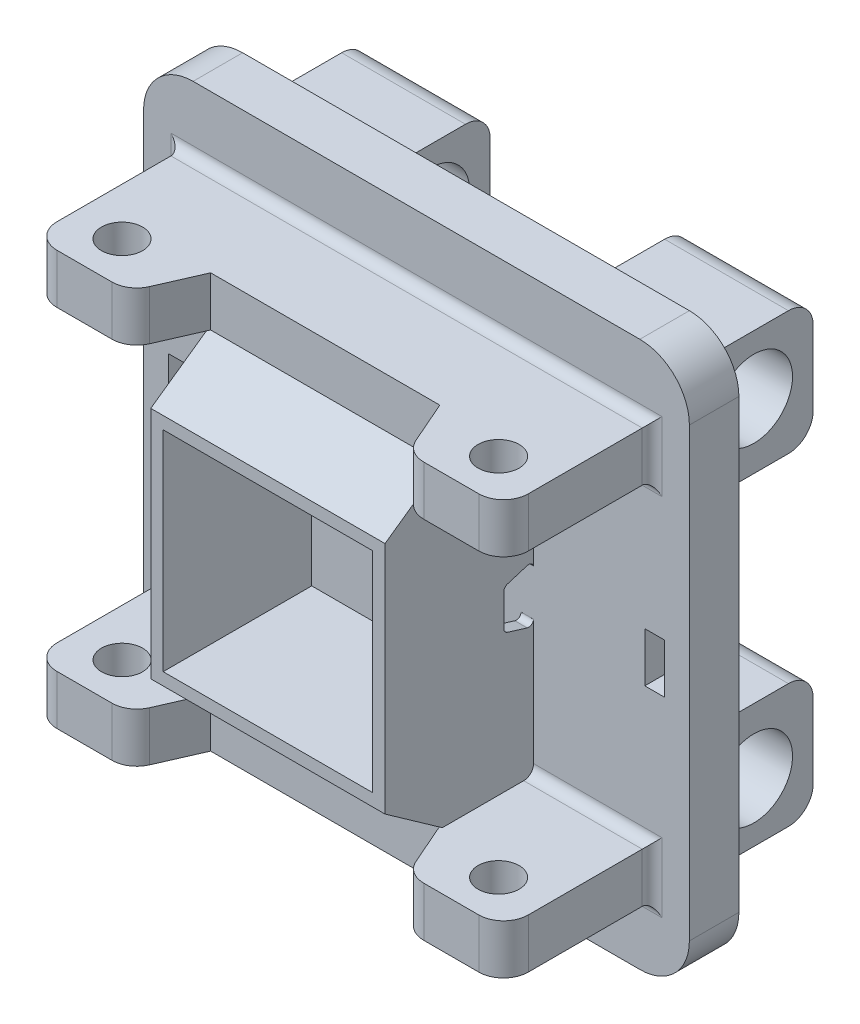
SolidWorks part; units mm, degrees
ref_plane "Piano frontale" through (0, 0, 0) normal (0, 0, 1) x (1, 0, 0)
ref_plane "Piano superiore" through (0, 0, 0) normal (0, 1, 0) x (1, 0, 0)
ref_plane "Piano destro" through (0, 0, 0) normal (1, 0, 0) x (0, 0, -1)
sketch "Schizzo1" plane through (0, 0, 0) normal (0, 0, 1) x (1, 0, 0)
  line L1 (-55.105, 55.105) -> (55.105, 55.105)
  line L2 (-55.105, 55.105) -> (-55.105, -55.105)
  line L3 (-55.105, -55.105) -> (55.105, -55.105)
  line L4 (55.105, 55.105) -> (55.105, -55.105)
  line L5 (-55.105, 55.105) -> (55.105, -55.105) construction
  line L6 (-55.105, -55.105) -> (55.105, 55.105) construction
  point P0 (0, 0)
  dimension "D1" = 110.21
  dimension "D2" = 110.21
extrude "Estrusione-Estrusione1" add sketch "Schizzo1" along normal blind 10
fillet "Raccordo1" radius 10 4 edges at (55.105, -55.105, 5) (-55.105, -55.105, 5) (55.105, 55.105, 5) (-55.105, 55.105, 5)
sketch "Schizzo5" plane through (0, 0, 0) normal (0, 0, -1) x (-1, 0, 0)
  line L0 (-55.105, 45.105) -> (55.105, 45.105) construction
  line L1 (55.105, 45.105) -> (-55.105, -45.105) construction
  line L2 (-55.105, -45.105) -> (-55.105, 45.105) construction
  line L3 (-55.105, -45.105) -> (55.105, -45.105) construction
  line L4 (55.105, -45.105) -> (-55.105, 45.105) construction
  line L5 (0, 57.1134) -> (0, 0) construction
  line L6 (0, 0) -> (66.1216, 0) construction
  arc A0 (-55.105, -45.105) -> (-45.105, -55.105) centre (-45.105, -45.105) ccw construction
ref_plane "Piano1" through (0, 0, 0) normal (0, 0, -1) x (-1, 0, 0)
sketch "Schizzo6" plane through (0, 0, 0) normal (0, 0, -1) x (-1, 0, 0)
  line L1 (-45.105, 45.105) -> (-20.105, 45.105)
  line L2 (-45.105, 45.105) -> (-45.105, 20.105)
  line L3 (-45.105, 20.105) -> (-20.105, 20.105)
  line L4 (-20.105, 45.105) -> (-20.105, 20.105)
  line L5 (0, 0) -> (127.9716, 0) construction
  line L6 (-20.105, -45.105) -> (-20.105, -20.105)
  line L7 (-45.105, -20.105) -> (-20.105, -20.105)
  line L8 (-45.105, -45.105) -> (-45.105, -20.105)
  line L9 (-45.105, -45.105) -> (-20.105, -45.105)
  dimension "D1" = 25
  dimension "D2" = 25
extrude "Estrusione-Estrusione2" add sketch "Schizzo6" along normal blind 25
fillet "Raccordo2" radius 5 2 edges at (32.605, 20.105, -25) (32.605, 45.105, -25)
sketch "Schizzo8" plane through (0, 0, 10) normal (0, 0, 1) x (1, 0, 0)
  line L1 (-21.15, 21.15) -> (21.15, 21.15)
  line L2 (-21.15, 21.15) -> (-21.15, -21.15)
  line L3 (-21.15, -21.15) -> (21.15, -21.15)
  line L4 (21.15, 21.15) -> (21.15, -21.15)
  line L5 (-21.15, 21.15) -> (21.15, -21.15) construction
  line L6 (-21.15, -21.15) -> (21.15, 21.15) construction
  line L7 (-23.65, 23.65) -> (23.65, 23.65)
  line L8 (-23.65, 23.65) -> (-23.65, -23.65)
  line L9 (-23.65, -23.65) -> (23.65, -23.65)
  line L10 (23.65, 23.65) -> (23.65, -23.65)
  line L11 (-23.65, 23.65) -> (23.65, -23.65) construction
  line L12 (-23.65, -23.65) -> (23.65, 23.65) construction
  point P0 (0, 0)
  point P6 (0, 0)
  dimension "D1" = 42.3
  dimension "D2" = 42.3
  dimension "D3" = 47.3
  dimension "D4" = 47.3
extrude "Estrusione-Estrusione4" add sketch "Schizzo8" along normal blind 30
sketch "Schizzo10" plane through (0, 0, 10) normal (0, 0, 1) x (1, 0, 0)
  line L5 (-47.5817, -31.821) -> (47.5817, -31.821)
  line L6 (-47.5817, -31.821) -> (-47.5817, -41.821)
  line L7 (-47.5817, -41.821) -> (47.5817, -41.821)
  line L8 (47.5817, -31.821) -> (47.5817, -41.821)
  line L9 (-47.5817, -31.821) -> (47.5817, -41.821) construction
  line L10 (-47.5817, -41.821) -> (47.5817, -31.821) construction
  point P5 (0, -36.821)
  dimension "D1" = 10
sketch "Schizzo16" plane through (0, 0, 0) normal (0, 0, -1) x (-1, 0, 0)
  line L0 (52.1761, 52.1761) -> (-52.1761, -52.1761) construction
  line L1 (0, 0) -> (43.631, 0) construction
  line L2 (52.1761, -52.1761) -> (-52.1761, 52.1761) construction
  line L4 (0, 47.0711) -> (0, -40) construction
  line L5 (-50.105, -5) -> (-46.105, -5)
  line L6 (-46.105, -5) -> (-46.105, 5)
  line L8 (-50.105, 5) -> (-46.105, 5)
  line L9 (-50.105, -5) -> (-50.105, 5)
  line L15 (0, 0) -> (-47.0711, 0) construction
  line L16 (55.105, 45.105) -> (55.105, -45.105) construction
  line L17 (50.105, -5) -> (46.105, -5)
  line L18 (50.105, -5) -> (50.105, 5)
  line L19 (50.105, 5) -> (46.105, 5)
  line L20 (46.105, -5) -> (46.105, 5)
  line L21 (50.105, -5) -> (46.105, 5) construction
  line L22 (50.105, 5) -> (46.105, -5) construction
  arc A0 (55.105, 45.105) -> (45.105, 55.105) centre (45.105, 45.105) ccw construction
  arc A1 (-55.105, -45.105) -> (-45.105, -55.105) centre (-45.105, -45.105) ccw construction
  arc A2 (45.105, -55.105) -> (55.105, -45.105) centre (45.105, -45.105) ccw construction
  arc A3 (-45.105, 55.105) -> (-55.105, 45.105) centre (-45.105, 45.105) ccw construction
  point P21 (0, -43)
  point P26 (48.105, 0)
  dimension "D4" = 4
  dimension "D5" = 10
  dimension "D6" = 9
extrude "Taglio-Estrusione11" cut sketch "Schizzo16" against normal blind 10
sketch "Schizzo20" plane through (45.105, 0, 0) normal (1, 0, 0) x (0, 0, -1)
  line L0 (0, 0) -> (81.2475, 0) construction
  circle A0 centre (13.0307, 33.1886) radius 7.8
  circle A1 centre (13.0307, -33.1886) radius 7.8
  dimension "D1" = 15.6
extrude "Taglio-Estrusione12" cut sketch "Schizzo20" against normal blind 25
fillet "Raccordo11" radius 5 1 edges at (32.605, -20.105, -25)
fillet "Raccordo12" radius 5 1 edges at (32.605, -45.105, -25)
mirror "Specchia17" about plane through (0, 0, 0) normal (1, 0, 0) of "Estrusione-Estrusione2"
mirror "Specchia19" about plane through (0, 0, 0) normal (1, 0, 0) of "Taglio-Estrusione12"
fillet "Raccordo13" radius 5 4 edges at (-32.605, -45.105, -25) (-32.605, -20.105, -25) (-32.605, 20.105, -25) (-32.605, 45.105, -25)
extrude "Estrusione-Estrusione5" add sketch "Schizzo10" along normal blind 30 contours L7 L8 L5 L6
sketch "Schizzo21" plane through (0, -41.821, 0) normal (0, -1, 0) x (1, 0, 0)
  line L0 (0, 0) -> (0, 52.7624) construction
  line L1 (-28.2038, 40) -> (-23.1374, 28.4269)
  line L2 (-47.5817, 40) -> (47.5817, 40) construction
  line L3 (-23.1374, 28.4269) -> (23.1374, 28.4269)
  line L4 (28.2038, 40) -> (23.1374, 28.4269)
  line L5 (-28.2038, 40) -> (28.2038, 40)
  circle A0 centre (-38.02, 31.4338) radius 4.15
  circle A1 centre (38.02, 31.4338) radius 4.15
  point P12 (0, 28.4269)
  point P16 (0, 28.4269)
  dimension "D1" = 8.3
extrude "Taglio-Estrusione13" cut sketch "Schizzo21" against normal blind 17
fillet "Raccordo15" radius 5 4 edges at (47.5817, -36.821, 40) (28.2038, -36.821, 40) (-28.2038, -36.821, 40) (-47.5817, -36.821, 40)
fillet "Raccordo16" radius 2 4 edges at (47.5817, -36.821, 10) (0, -31.821, 10) (0, -41.821, 10) (-47.5817, -36.821, 10)
mirror "Specchia20" about plane through (0, 0, 0) normal (0, 1, 0) of "Taglio-Estrusione13", "Raccordo15", "Estrusione-Estrusione5", "Raccordo16"
sketch "Schizzo28" plane through (21.15, 0, 0) normal (-1, 0, 0) x (0, 0, 1)
  line L0 (10, 21.1895) -> (10, -21.0053) construction
  line L1 (10, -45.105) -> (10, 45.105) construction
  line L2 (10, 4.7736) -> (10, -4.5894)
  arc A0 (10, -4.5894) -> (10, 4.7736) centre (10, 0.0921) ccw
sketch "Schizzo29" plane through (-23.65, 0, 0) normal (-1, 0, 0) x (0, 0, 1)
  line L0 (40, 23.65) -> (28.4269, 31.821)
  line L1 (28.4269, 31.821) -> (10, 31.821)
  line L2 (10, 29.821) -> (10, 43.821) construction
  line L3 (10, 31.821) -> (10, 23.65)
  line L4 (10, 23.65) -> (40, 23.65)
extrude "Estrusione-Estrusione7" add sketch "Schizzo29" against normal up to surface (47.3 mm away) contours L0 L1 L3 L4 up to face at (23.65, 0, 25)
mirror "Specchia22" about plane through (0, 0, 0) normal (0, 1, 0) of "Estrusione-Estrusione7"
sketch "Schizzo30" plane through (23.65, 0, 0) normal (1, 0, 0) x (0, 0, -1)
  line L1 (-10, -18.0505) -> (-10, 24.9175) construction
  line L2 (-10, -29.821) -> (-10, 29.821) construction
  line L3 (-16, -4) -> (-10, -5.8439)
  line L6 (-10, -4) -> (-10, 4)
  line L8 (-16, -4) -> (-16, 4)
  line L9 (-10, -5.8439) -> (-10, -4)
  line L11 (-10, 5.8439) -> (-10, 4)
  line L12 (-16, 4) -> (-10, 5.8439)
extrude "Taglio-Estrusione16" cut sketch "Schizzo30" against normal blind 8.05
fillet "Raccordo18" radius 1 4 edges at (22.4, 5.8439, 10) (22.4, -5.8439, 10) (22.4, 4, 16) (22.4, -4, 16)
extrude "Taglio-Estrusione14" cut sketch "Schizzo28" against normal blind 17
